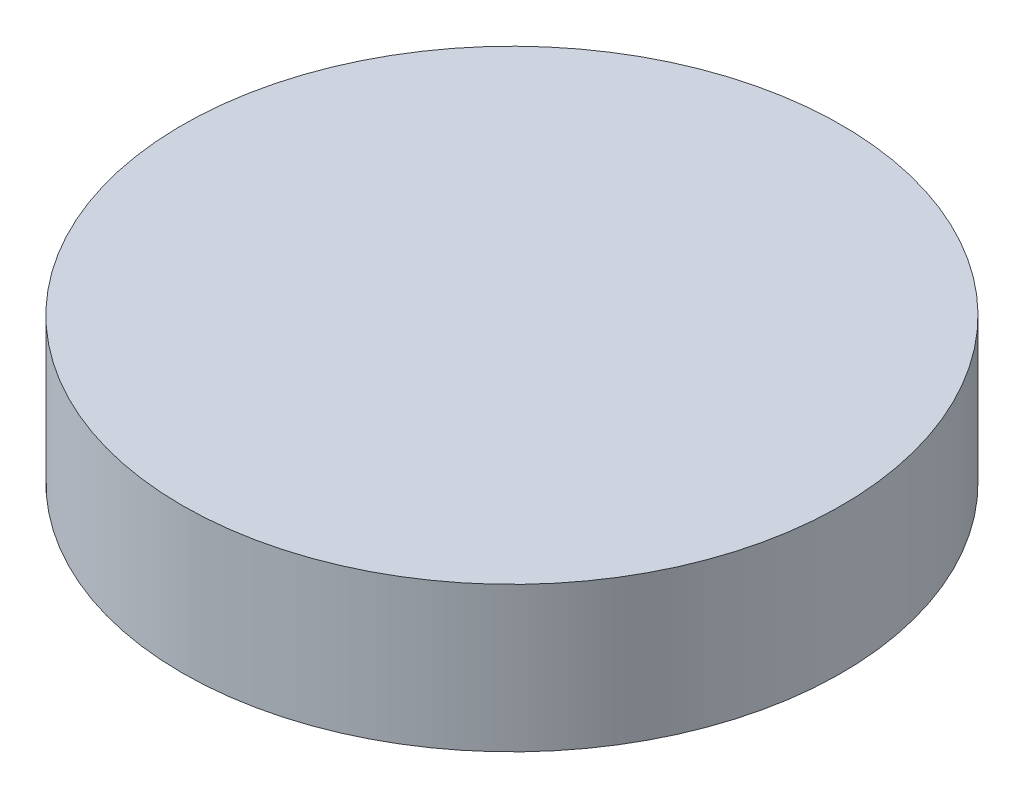
SolidWorks part; units mm, degrees
ref_plane "Ebene vorne" through (0, 0, 0) normal (0, 0, 1) x (1, 0, 0)
ref_plane "Ebene oben" through (0, 0, 0) normal (0, 1, 0) x (1, 0, 0)
ref_plane "Ebene rechts" through (0, 0, 0) normal (1, 0, 0) x (0, 0, -1)
sketch "Sketch1" plane through (0, 0, 0) normal (0, 1, 0) x (1, 0, 0)
  circle A0 centre (0, 0) radius 72.7
  dimension "D1" = 145.4
extrude "Boss-Extrude1" add sketch "Sketch1" along normal blind 32
